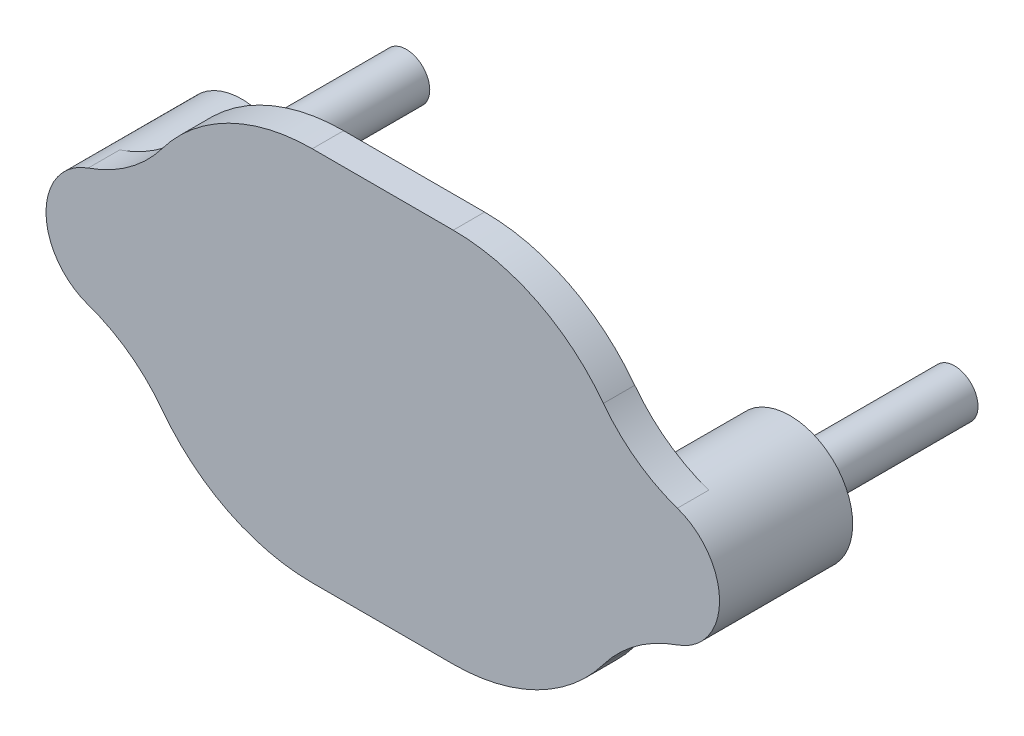
SolidWorks part; units mm, degrees
ref_plane "前视基准面" through (0, 0, 0) normal (0, 0, 1) x (1, 0, 0)
ref_plane "上视基准面" through (0, 0, 0) normal (0, 1, 0) x (1, 0, 0)
ref_plane "右视基准面" through (0, 0, 0) normal (1, 0, 0) x (0, 0, -1)
sketch "草图1" plane through (0, 0, 0) normal (0, 0, 1) x (1, 0, 0)
  line L0 (0, 0) -> (23.5174, 0) construction
  line L1 (0, 0) -> (0, 15) construction
  line L8 (-4.5, 12) -> (4.5, 12)
  line L9 (-4.5, -12) -> (4.5, -12)
  arc A0 (4.5, 12) -> (14.0874, 7.2168) centre (4.5, 0) cw
  arc A1 (18.8077, -3.7802) -> (18.8077, 3.7802) centre (17.5, 0) ccw
  arc A2 (14.0874, 7.2168) -> (18.8077, 3.7802) centre (22.0769, 13.2307) ccw
  arc A3 (-14.0874, 7.2168) -> (-18.8077, 3.7802) centre (-22.0769, 13.2307) cw
  arc A4 (-4.5, 12) -> (-14.0874, 7.2168) centre (-4.5, 0) ccw
  arc A5 (14.0874, -7.2168) -> (18.8077, -3.7802) centre (22.0769, -13.2307) cw
  arc A6 (4.5, -12) -> (14.0874, -7.2168) centre (4.5, 0) ccw
  arc A7 (-4.5, -12) -> (-14.0874, -7.2168) centre (-4.5, 0) cw
  arc A8 (-14.0874, -7.2168) -> (-18.8077, -3.7802) centre (-22.0769, -13.2307) ccw
  arc A9 (-18.8077, -3.7802) -> (-18.8077, 3.7802) centre (-17.5, 0) cw
  point P22 (0, 7.5)
  dimension "D2" = 8
  dimension "D6" = 12
  dimension "D7" = 10
  dimension "D4" = 17.5
extrude "凸台-拉伸1" add sketch "草图1" against normal blind 2 contours A2 A1 A5 A6 L9 A7 A8 A9 A3 A4 L8 A0
sketch "草图2" plane through (0, 0, -2) normal (0, 0, -1) x (-1, 0, 0)
  circle A0 centre (17.5, 0) radius 4
  circle A1 centre (-17.5, 0) radius 4
extrude "凸台-拉伸2" add sketch "草图2" along normal blind 6.5
sketch "草图3" plane through (0, 0, -8.5) normal (0, 0, -1) x (-1, 0, 0)
  circle A0 centre (17.5, 0) radius 1.5
  circle A1 centre (-17.5, 0) radius 1.5
  dimension "D1" = 3
  dimension "D2" = 3
extrude "凸台-拉伸3" add sketch "草图3" along normal blind 10.5
